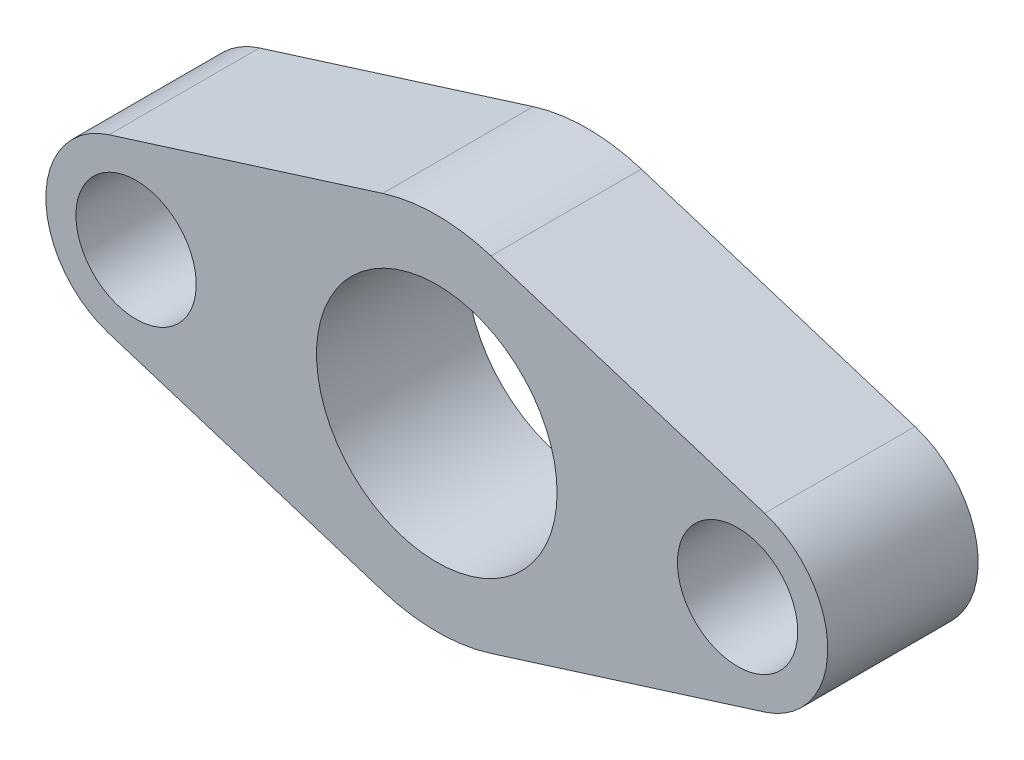
SolidWorks part; units mm, degrees
material "Cast Alloy Steel"
ref_plane "Front Plane" through (0, 0, 0) normal (0, 0, 1) x (1, 0, 0)
ref_plane "Top Plane" through (0, 0, 0) normal (0, 1, 0) x (1, 0, 0)
ref_plane "Right Plane" through (0, 0, 0) normal (1, 0, 0) x (0, 0, -1)
sketch "Sketch1" plane through (0, 0, 0) normal (0, 0, 1) x (1, 0, 0)
  line L0 (80, 4.3963) -> (80, 74992.4046) construction
  line L1 (76.7252, 50) -> (75064.7334, 50) construction
  line L2 (134.5, 64.3091) -> (89, 78.6182)
  line L3 (89, 21.3818) -> (134.5, 35.6909)
  line L4 (71, 21.3818) -> (25.5, 35.6909)
  line L5 (25.5, 64.3091) -> (71, 78.6182)
  circle A0 centre (80, 50) radius 20
  arc A1 (89, 78.6182) -> (71, 78.6182) centre (80, 50) ccw
  circle A2 centre (130, 50) radius 10
  arc A3 (134.5, 35.6909) -> (134.5, 64.3091) centre (130, 50) ccw
  arc A4 (25.5, 35.6909) -> (25.5, 64.3091) centre (30, 50) cw
  circle A5 centre (30, 50) radius 10
  arc A6 (71, 21.3818) -> (89, 21.3818) centre (80, 50) ccw
  dimension "D4" = 60
  dimension "D5" = 40
  dimension "D6" = 30
  dimension "D7" = 20
  dimension "D1" = 80
  dimension "D2" = 50
  dimension "D3" = 100
extrude "Boss-Extrude1" add sketch "Sketch1" along normal mid plane 25
